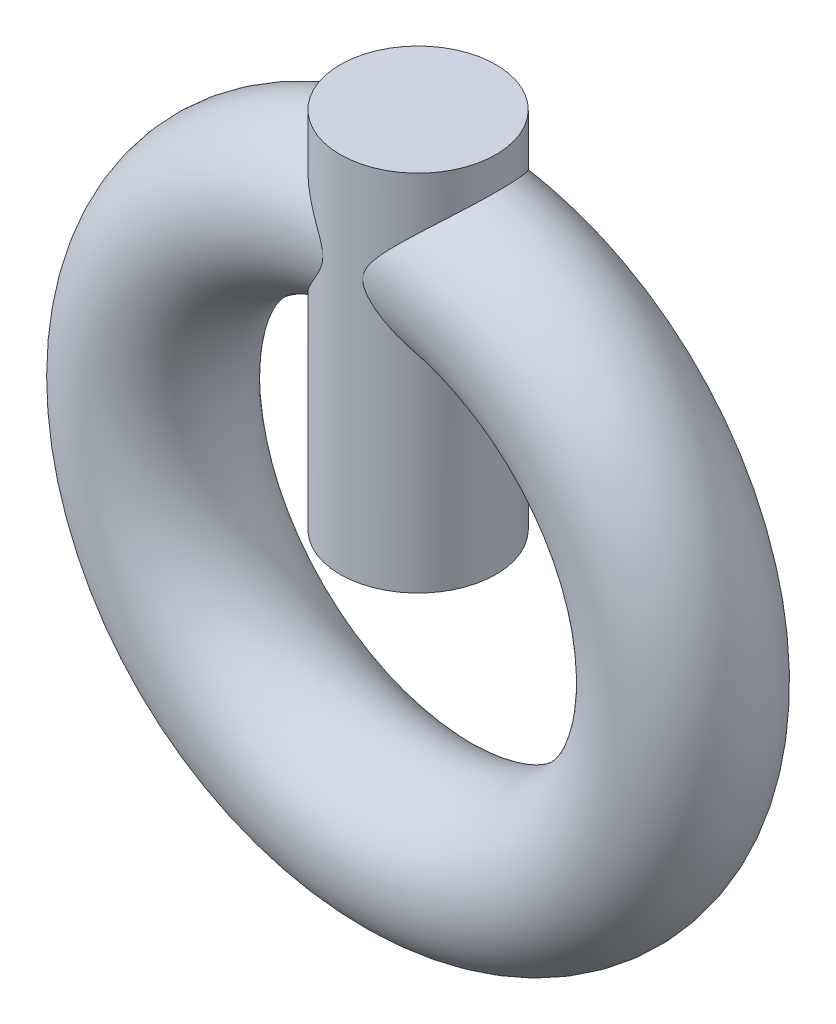
SolidWorks part; units mm, degrees
ref_plane "前视基准面" through (0, 0, 0) normal (0, 0, 1) x (1, 0, 0)
ref_plane "上视基准面" through (0, 0, 0) normal (0, 1, 0) x (1, 0, 0)
ref_plane "右视基准面" through (0, 0, 0) normal (1, 0, 0) x (0, 0, -1)
sketch "草图1" plane through (0, 0, 0) normal (0, 0, 1) x (1, 0, 0)
  circle A0 centre (0, 0) radius 5
  dimension "D1" = 10
sketch "草图3" plane through (0, 0, 0) normal (1, 0, 0) x (0, 0, -1)
  line L0 (0, 5) -> (0, -5) construction
  circle A0 centre (0, 5.1) radius 1.45
  dimension "D1" = 2.9
sweep "扫描1" add profiles "草图3" path "草图1"
sketch "草图6" plane through (0, 0, 0) normal (0, 1, 0) x (1, 0, 0)
  circle A0 centre (0, 0) radius 1.5
extrude "凸台-拉伸1" add sketch "草图6" along normal blind 7
